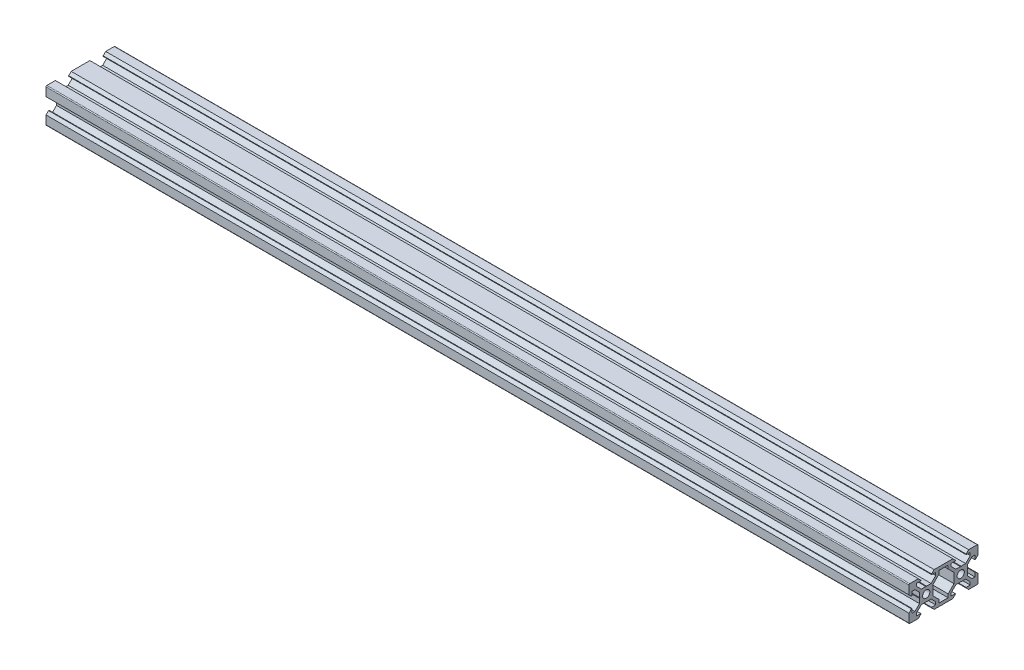
SolidWorks part; units mm, degrees
material "6061-T6 (SS)"
ref_plane "Top" through (0, 0, 0) normal (0, 0, 1) x (1, 0, 0)
ref_plane "Front" through (0, 0, 0) normal (0, 1, 0) x (1, 0, 0)
ref_plane "Right" through (0, 0, 0) normal (1, 0, 0) x (0, 0, -1)
sketch "Profile Sketch" plane through (0, 0, 0) normal (1, 0, 0) x (0, 0, -1)
  line L0 (5.42, 10) -> (-5.42, 10)
  line L1 (-4.5, 8.2) -> (-4.5, 6.56)
  line L2 (-4.5, 6.56) -> (-7.16, 3.9)
  line L3 (-7.16, 3.9) -> (-9.79, 3.9)
  line L4 (-9.79, 3.9) -> (-10, 3.69)
  line L5 (2.7, 8.2) -> (-2.7, 8.2)
  line L6 (-2.7, 8.2) -> (-2.7, 6.2387)
  line L7 (-2.7, 6.2387) -> (-6.1, 2.8387)
  line L8 (-6.1, 2.8387) -> (-6.1, -0.21)
  line L9 (-6.875, 8.545) -> (-6.875, 8.2)
  line L10 (-6.875, 8.2) -> (-4.5, 8.2)
  line L11 (-6.875, 8.545) -> (-5.42, 10)
  line L12 (0, -10) -> (0, 10) construction
  line L13 (-20, 0) -> (20, 0) construction
  line L14 (-10, -10) -> (-10, 10) construction
  line L15 (-6.875, -8.545) -> (-5.42, -10)
  line L16 (-6.875, -8.2) -> (-4.5, -8.2)
  line L17 (-6.875, -8.545) -> (-6.875, -8.2)
  line L18 (-2.7, -6.2387) -> (-6.1, -2.8387)
  line L19 (-2.7, -8.2) -> (-2.7, -6.2387)
  line L20 (2.7, -8.2) -> (-2.7, -8.2)
  line L21 (-7.16, -3.9) -> (-9.79, -3.9)
  line L22 (-4.5, -6.56) -> (-7.16, -3.9)
  line L23 (-4.5, -8.2) -> (-4.5, -6.56)
  line L24 (5.42, -10) -> (-5.42, -10)
  line L25 (-10, 0) -> (-20, 10) construction
  line L26 (-18.545, 3.125) -> (-18.2, 3.125)
  line L27 (-13.125, -8.545) -> (-13.125, -8.2)
  line L28 (-13.125, -8.2) -> (-15.5, -8.2)
  line L29 (-13.125, -8.545) -> (-14.58, -10)
  line L30 (-15.5, -8.2) -> (-15.5, -6.56)
  line L31 (-15.5, -6.56) -> (-12.84, -3.9)
  line L32 (-12.84, -3.9) -> (-10.21, -3.9)
  line L33 (-20, 4.58) -> (-20, 9.5)
  line L34 (-13.9, 2.8387) -> (-13.9, 0.21)
  line L35 (-16.56, 5.5) -> (-13.9, 2.8387)
  line L36 (-12.84, 3.9) -> (-10.21, 3.9)
  line L37 (-15.5, 6.56) -> (-12.84, 3.9)
  line L38 (-15.5, 8.2) -> (-15.5, 6.56)
  line L39 (-13.125, 8.545) -> (-14.58, 10)
  line L40 (-13.125, 8.2) -> (-15.5, 8.2)
  line L41 (-13.125, 8.545) -> (-13.125, 8.2)
  line L42 (-18.2, 3.125) -> (-18.2, 5.5)
  line L43 (-18.545, 3.125) -> (-20, 4.58)
  line L44 (-18.2, 5.5) -> (-16.56, 5.5)
  line L45 (-14.58, 10) -> (-19.5, 10)
  line L46 (-16.56, -5.5) -> (-13.9, -2.8387)
  line L47 (-14.58, -10) -> (-19.5, -10)
  line L48 (-18.2, -5.5) -> (-16.56, -5.5)
  line L49 (-18.545, -3.125) -> (-20, -4.58)
  line L50 (-18.2, -3.125) -> (-18.2, -5.5)
  line L51 (-20, -4.58) -> (-20, -9.5)
  line L52 (-18.545, -3.125) -> (-18.2, -3.125)
  line L53 (10, -10) -> (10, 10) construction
  line L54 (18.545, -3.125) -> (18.2, -3.125)
  line L55 (20, -4.58) -> (20, -9.5)
  line L56 (18.2, -3.125) -> (18.2, -5.5)
  line L57 (18.545, -3.125) -> (20, -4.58)
  line L58 (18.2, -5.5) -> (16.56, -5.5)
  line L59 (14.58, -10) -> (19.5, -10)
  line L60 (16.56, -5.5) -> (13.9, -2.8387)
  line L61 (14.58, 10) -> (19.5, 10)
  line L62 (18.2, 5.5) -> (16.56, 5.5)
  line L63 (18.545, 3.125) -> (20, 4.58)
  line L64 (18.2, 3.125) -> (18.2, 5.5)
  line L65 (13.125, 8.545) -> (13.125, 8.2)
  line L66 (13.125, 8.2) -> (15.5, 8.2)
  line L67 (13.125, 8.545) -> (14.58, 10)
  line L68 (15.5, 8.2) -> (15.5, 6.56)
  line L69 (15.5, 6.56) -> (12.84, 3.9)
  line L70 (12.84, 3.9) -> (10.21, 3.9)
  line L71 (16.56, 5.5) -> (13.9, 2.8387)
  line L72 (13.9, 2.8387) -> (13.9, 0.21)
  line L73 (20, 4.58) -> (20, 9.5)
  line L74 (12.84, -3.9) -> (10.21, -3.9)
  line L75 (15.5, -6.56) -> (12.84, -3.9)
  line L76 (15.5, -8.2) -> (15.5, -6.56)
  line L77 (13.125, -8.545) -> (14.58, -10)
  line L78 (13.125, -8.2) -> (15.5, -8.2)
  line L79 (13.125, -8.545) -> (13.125, -8.2)
  line L80 (18.545, 3.125) -> (18.2, 3.125)
  line L81 (4.5, -8.2) -> (4.5, -6.56)
  line L82 (4.5, -6.56) -> (7.16, -3.9)
  line L83 (7.16, -3.9) -> (9.79, -3.9)
  line L84 (2.7, -8.2) -> (2.7, -6.2387)
  line L85 (2.7, -6.2387) -> (6.1, -2.8387)
  line L86 (6.875, -8.545) -> (6.875, -8.2)
  line L87 (6.875, -8.2) -> (4.5, -8.2)
  line L88 (6.875, -8.545) -> (5.42, -10)
  line L89 (6.875, 8.545) -> (5.42, 10)
  line L90 (6.875, 8.2) -> (4.5, 8.2)
  line L91 (6.875, 8.545) -> (6.875, 8.2)
  line L92 (6.1, 2.8387) -> (6.1, -0.21)
  line L93 (2.7, 6.2387) -> (6.1, 2.8387)
  line L94 (2.7, 8.2) -> (2.7, 6.2387)
  line L95 (9.79, 3.9) -> (10, 3.69)
  line L96 (7.16, 3.9) -> (9.79, 3.9)
  line L97 (4.5, 6.56) -> (7.16, 3.9)
  line L98 (4.5, 8.2) -> (4.5, 6.56)
  line L99 (-10, 3.69) -> (-10.21, 3.9)
  line L100 (-10, -3.69) -> (-10.21, -3.9)
  line L101 (-9.79, -3.9) -> (-10, -3.69)
  line L102 (-13.9, -0.21) -> (-13.69, 0)
  line L103 (-13.69, 0) -> (-13.9, 0.21)
  line L104 (-13.9, -0.21) -> (-13.9, -2.8387)
  line L105 (-6.1, -0.21) -> (-6.31, 0)
  line L106 (-6.31, 0) -> (-6.1, -0.21)
  line L107 (-6.1, -0.21) -> (-6.1, -2.8387)
  line L108 (6.31, 0) -> (6.1, -0.21)
  line L109 (6.1, -0.21) -> (6.31, 0)
  line L110 (13.69, 0) -> (13.9, 0.21)
  line L111 (13.9, -0.21) -> (13.69, 0)
  line L112 (9.79, -3.9) -> (10, -3.69)
  line L113 (10, -3.69) -> (10.21, -3.9)
  line L114 (10, 3.69) -> (10.21, 3.9)
  line L115 (6.1, -0.21) -> (6.1, -2.8387)
  line L116 (13.9, -0.21) -> (13.9, -2.8387)
  line L118 (20, -10) -> (20, 10) construction
  line L119 (20, -10) -> (-20, -10) construction
  line L120 (-20, -10) -> (-20, 10) construction
  line L121 (20, 10) -> (-20, 10) construction
  line L122 (20, -10) -> (-20, 10) construction
  line L123 (-20, -10) -> (20, 10) construction
  circle A0 centre (-10, 0) radius 2.1
  arc A1 (-19.5, 10) -> (-20, 9.5) centre (-19.5, 9.5) ccw
  arc A2 (-19.5, -10) -> (-20, -9.5) centre (-19.5, -9.5) cw
  arc A3 (19.5, -10) -> (20, -9.5) centre (19.5, -9.5) ccw
  arc A4 (19.5, 10) -> (20, 9.5) centre (19.5, 9.5) cw
  circle A5 centre (10, 0) radius 2.1
  point P35 (-2.4957, 0)
  point P108 (0, -8.2)
  point P119 (0, 8.2)
  point P123 (2.4957, 0)
  point P131 (0, 0)
  point P143 (0, 0)
  dimension "D4" = 5.42
  dimension "D5" = 40
  dimension "D6" = 4.2
  dimension "D16" = 0.5
  dimension "D1" = 0.21
  dimension "D2" = 45
  dimension "D3" = 20
  dimension "D7" = 1.5
  dimension "D8" = 1.8
  dimension "D9" = 10
  dimension "D10" = 3.9
  dimension "D11" = 3.9
  dimension "D12" = 1.8
  dimension "D13" = 3.125
  dimension "D14" = 5.5
  dimension "D15" = 1.64
  dimension "D17" = 5.4
extrude "Profile Extrude" add sketch "Profile Sketch" along normal blind 500 contours A4 L61 L67 L65 L66 L68 L69 L70 L114 L95 L96 L97 L98 L90 L91 L89 L0 L11 L9 L10 L1 L2 L3 L4 L99 L36 L37 L38 L40 L41 L39 L45 A1 L33 L43 L26 L42 L44 L35 L34 L103 L102 L104 L46 L48 L50 L52 L49 L51 A2 L47
equation "\"M2x0.4_Tap_Hole_75\"= 1.6"
